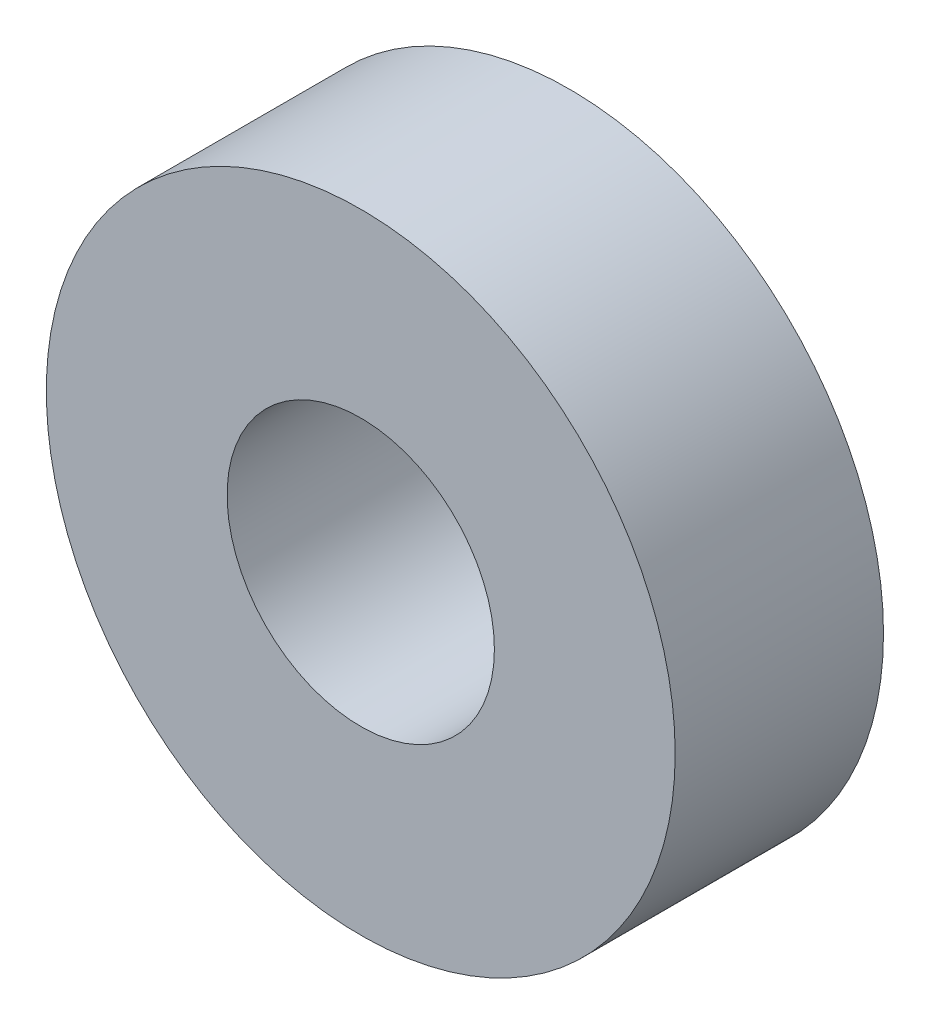
SolidWorks part; units mm, degrees
ref_plane "Front Plane" through (0, 0, 0) normal (0, 0, 1) x (1, 0, 0)
ref_plane "Top Plane" through (0, 0, 0) normal (0, 1, 0) x (1, 0, 0)
ref_plane "Right Plane" through (0, 0, 0) normal (1, 0, 0) x (0, 0, -1)
sketch "Sketch1" plane through (0, 0, 0) normal (0, 0, 1) x (1, 0, 0)
  circle A0 centre (0, 0) radius 20
  circle A1 centre (0, 0) radius 8.5
  dimension "D1" = 17
  dimension "D2" = 40
extrude "Boss-Extrude1" add sketch "Sketch1" along normal blind 13.25
